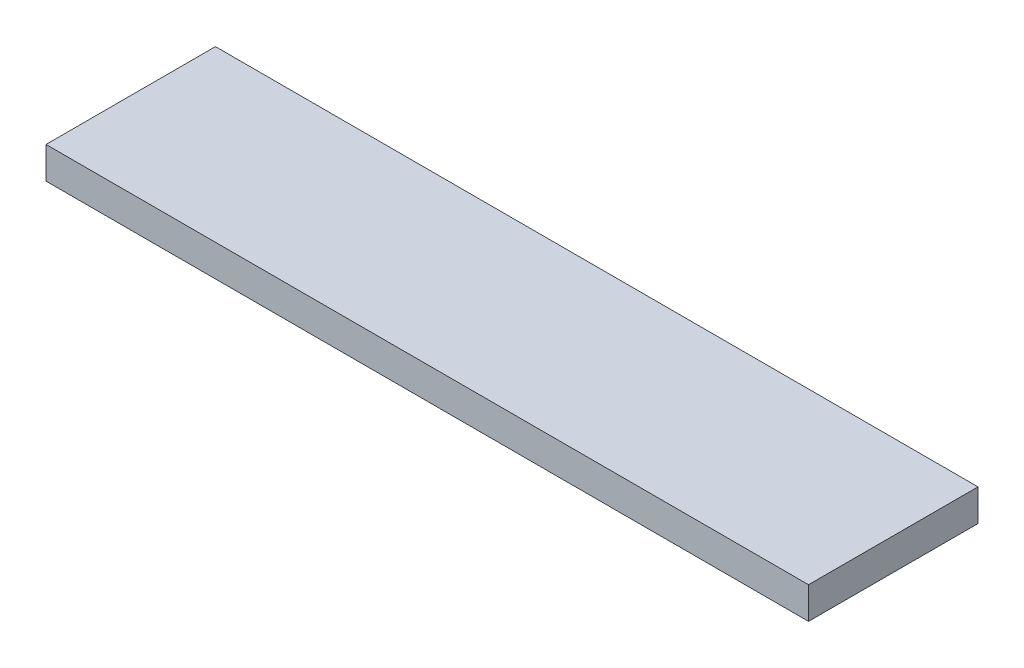
SolidWorks part; units mm, degrees
ref_plane "Front Plane" through (0, 0, 0) normal (0, 0, 1) x (1, 0, 0)
ref_plane "Top Plane" through (0, 0, 0) normal (0, 1, 0) x (1, 0, 0)
ref_plane "Right Plane" through (0, 0, 0) normal (1, 0, 0) x (0, 0, -1)
sketch "Sketch1" plane through (0, 0, 0) normal (0, 0, 1) x (1, 0, 0)
  line L1 (-61.9125, -15.875) -> (52.3875, -15.875)
  line L2 (-61.9125, -15.875) -> (-61.9125, -11.1125)
  line L3 (-61.9125, -11.1125) -> (52.3875, -11.1125)
  line L4 (52.3875, -15.875) -> (52.3875, -11.1125)
  dimension "D1" = 4.7625
extrude "Boss-Extrude1" add sketch "Sketch1" along normal blind 25.4
